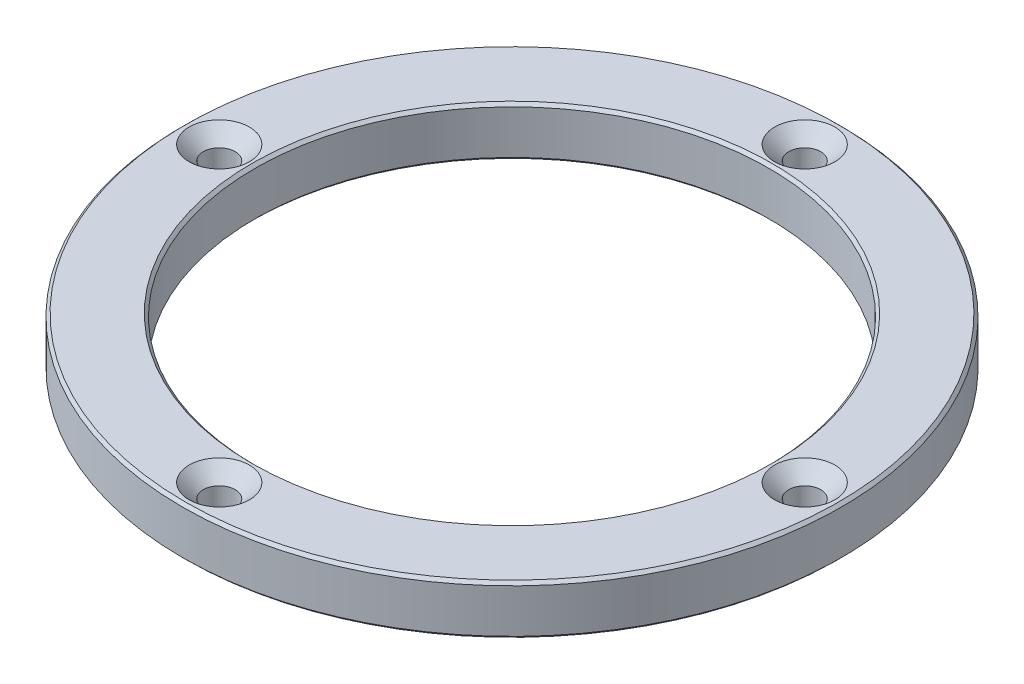
SolidWorks part; units mm, degrees
ref_plane "正面" through (0, 0, 0) normal (0, 0, 1) x (1, 0, 0)
ref_plane "平面" through (0, 0, 0) normal (0, 1, 0) x (1, 0, 0)
ref_plane "右側面" through (0, 0, 0) normal (1, 0, 0) x (0, 0, -1)
sketch "ｽｹｯﾁ1" plane through (0, 0, 0) normal (0, 1, 0) x (1, 0, 0)
  circle A0 centre (0, 0) radius 44.35
  circle A1 centre (0, 0) radius 56.85
  dimension "D1" = 88.7
  dimension "D2" = 12.5
extrude "ﾎﾞｽ - 押し出し1" add sketch "ｽｹｯﾁ1" along normal mid plane 8.55
chamfer "面取り1" distance 0.5 angle 45 4 edges at (0, -4.275, 44.35) (0, 4.275, 44.35) (0, -4.275, 56.85) (0, 4.275, 56.85)
sketch "ｽｹｯﾁ2" plane through (0, 4.275, 0) normal (0, 1, 0) x (1, 0, 0)
  line L0 (0, 0) -> (0, 50.5) construction
  circle A0 centre (0, 50.5) radius 2.5
  dimension "D2" = 5
  dimension "D1" = 50.5
extrude "ｶｯﾄ - 押し出し1" cut sketch "ｽｹｯﾁ2" against normal blind 10
hole_wizard "M5 丸皿ねじ用皿穴1" positions "3Dｽｹｯﾁ1" profile "ｽｹｯﾁ3" countersink size "M5" standard "ISO"
sketch3d "3Dｽｹｯﾁ1"
  line L0 (0, -4.275, -50.5) -> (0, 4.275, -50.5) construction
  point P0 (0, 4.275, -50.5)
sketch "ｽｹｯﾁ3" plane through (0, 4.275, -50.5) normal (1, 0, 0) x (0, 0, 1)
  line L0 (0, 0) -> (0, 11.6524)
  line L1 (0, 11.6524) -> (2.75, 10)
  line L2 (2.75, 10) -> (2.75, 2.45)
  line L3 (2.75, 2.45) -> (5.2, 0)
  line L5 (5.2, 0) -> (0, 0)
  line L6 (-2.75, 2.45) -> (-5.2, 0) construction
  line L10 (0, 11.6524) -> (-2.75, 10) construction
  line L11 (0, -6.35) -> (0, 107.95) construction
  dimension "穴の直径" = 5.5
  dimension "穴の深さ" = 10
  dimension "表面の皿穴の直径" = 10.4
  dimension "表面の皿穴の角度" = 90
  dimension "ﾄﾞﾘﾙ角度" = 118
pattern_circular "円形ﾊﾟﾀｰﾝ1" count 4 over 360 about axis through (0, 0, 0) along (0, 1, 0) of "M5 丸皿ねじ用皿穴1"
